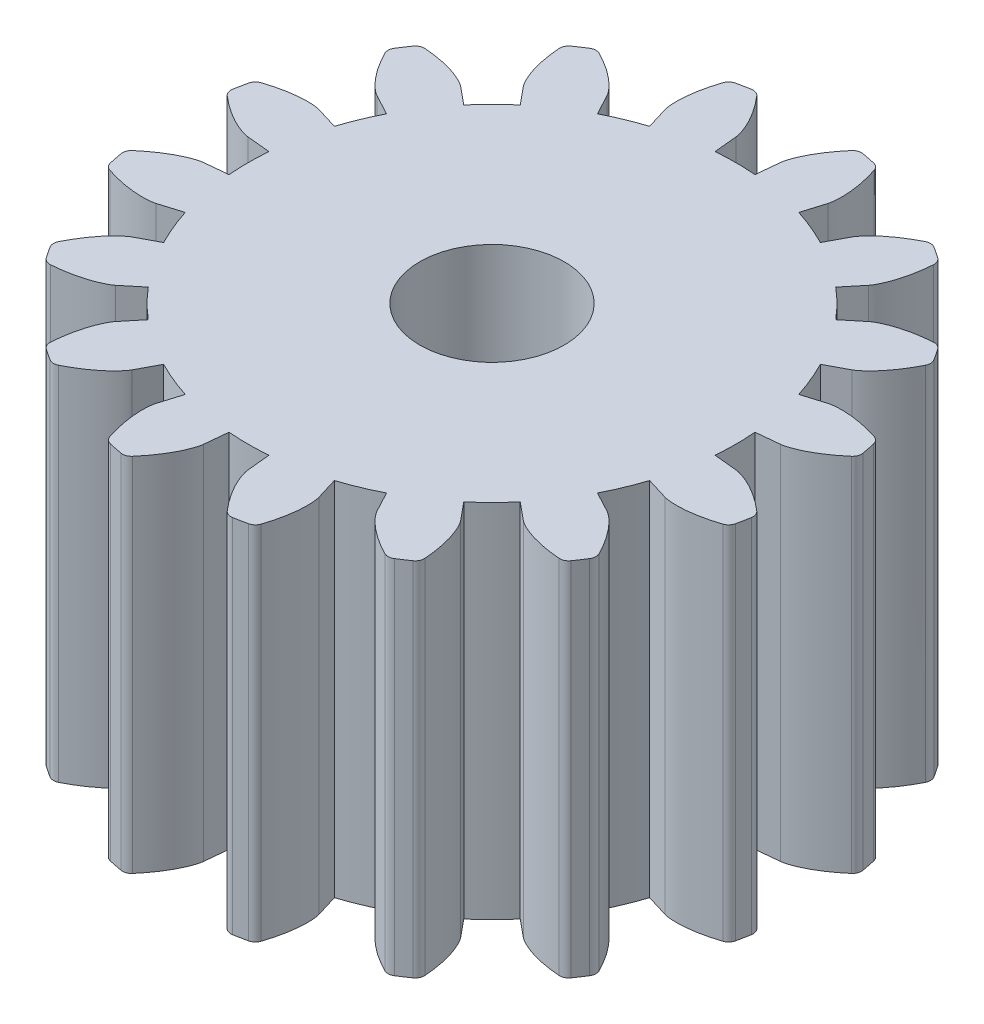
SolidWorks part; units mm, degrees
ref_plane "Front Plane" through (0, 0, 0) normal (0, 0, 1) x (1, 0, 0)
ref_plane "Top Plane" through (0, 0, 0) normal (0, 1, 0) x (1, 0, 0)
ref_plane "Right Plane" through (0, 0, 0) normal (1, 0, 0) x (0, 0, -1)
sketch "Sketch4" plane through (0, 0, 0) normal (0, 1, 0) x (1, 0, 0)
  circle A0 centre (0, 0) radius 9
  dimension "D1" = 18
extrude "Boss-Extrude2" add sketch "Sketch4" along normal blind 10.16 separate body contours A0
sketch "Sketch6" plane through (0, 10.16, 0) normal (0, 1, 0) x (1, 0, 0)
  circle A0 centre (0, 0) radius 2.032
  dimension "D1" = 4.064
extrude "Cut-Extrude1" cut sketch "Sketch6" against normal blind 10.16 contours A0
sketch "Sketch7" plane through (0, 10.16, 0) normal (0, 1, 0) x (1, 0, 0)
  line L0 (0, 0) -> (10.4884, 0) construction
  line L1 (7.4915, 0.6253) -> (6.835, 0.5613)
  line L3 (7.4915, -0.6253) -> (6.835, -0.5613)
  circle A0 centre (0, 0) radius 8 construction
  circle A1 centre (0, 0) radius 7.493 construction
  circle A2 centre (0, 0) radius 6.858 construction
  arc A3 (6.835, 0.5613) -> (6.835, -0.5613) centre (0, 0) cw
  arc A4 (8.886, 1.4282) -> (9.071, 0) centre (5.3028, 0.2379) cw
  arc A5 (8.886, -1.4282) -> (9.071, 0) centre (5.3028, -0.2379) ccw
  spline S0 degree 4 poles (7.4915, 0.6253) (7.4939, 0.6255) (7.5006, 0.6263) (7.5213, 0.6293) (7.5618, 0.6371) (7.6114, 0.6494) (7.668, 0.6661) (7.7222, 0.6842) (7.7683, 0.7009) (7.814, 0.7188) (7.8593, 0.7375) (7.9138, 0.7615) (7.9787, 0.7919) (8.0538, 0.8298) (8.1382, 0.8757) (8.2231, 0.9255) (8.3059, 0.9769) (8.3884, 1.0317) (8.4676, 1.0867) (8.5487, 1.1467) (8.6229, 1.2035) (8.7048, 1.2702) (8.7705, 1.3249) (8.8557, 1.4004) (8.9056, 1.4459) (8.9634, 1.5004) (8.9888, 1.5251) (9.0044, 1.5403) knots 0 0 0 0 0 0.005377 0.015084 0.04661 0.092111 0.119476 0.146842 0.174209 0.201575 0.228941 0.256307 0.307035 0.361767 0.4165 0.471232 0.525964 0.580697 0.635429 0.690161 0.744894 0.799626 0.854358 0.909091 0.954545 1 1 1 1 1 construction
  spline S1 degree 4 poles (7.4915, 0.6253) (7.4939, 0.6255) (7.5006, 0.6263) (7.5213, 0.6293) (7.5618, 0.6371) (7.6114, 0.6494) (7.668, 0.6661) (7.7222, 0.6842) (7.7683, 0.7009) (7.814, 0.7188) (7.8593, 0.7375) (7.9138, 0.7615) (7.9787, 0.7919) (8.0538, 0.8298) (8.1382, 0.8757) (8.2231, 0.9255) (8.3059, 0.9769) (8.3884, 1.0317) (8.4676, 1.0867) (8.5487, 1.1467) (8.6229, 1.2035) (8.7048, 1.2702) (8.7705, 1.3249) (8.8372, 1.384) (8.8695, 1.4132) (8.886, 1.4282) knots 0 0 0 0 0 0.005377 0.015084 0.04661 0.092111 0.119476 0.146842 0.174209 0.201575 0.228941 0.256307 0.307035 0.361767 0.4165 0.471232 0.525964 0.580697 0.635429 0.690161 0.744894 0.799626 0.854358 0.909091 0.909091 0.909091 0.909091 0.909091
  spline S2 degree 4 poles (7.4915, -0.6253) (7.4939, -0.6255) (7.5006, -0.6263) (7.5213, -0.6293) (7.5618, -0.6371) (7.6114, -0.6494) (7.668, -0.6661) (7.7222, -0.6842) (7.7683, -0.7009) (7.814, -0.7188) (7.8593, -0.7375) (7.9138, -0.7615) (7.9787, -0.7919) (8.0538, -0.8298) (8.1382, -0.8757) (8.2231, -0.9255) (8.3059, -0.9769) (8.3884, -1.0317) (8.4676, -1.0867) (8.5487, -1.1467) (8.6229, -1.2035) (8.7048, -1.2702) (8.7705, -1.3249) (8.8372, -1.384) (8.8695, -1.4132) (8.886, -1.4282) knots 0 0 0 0 0 0.005377 0.015084 0.04661 0.092111 0.119476 0.146842 0.174209 0.201575 0.228941 0.256307 0.307035 0.361767 0.4165 0.471232 0.525964 0.580697 0.635429 0.690161 0.744894 0.799626 0.854358 0.909091 0.909091 0.909091 0.909091 0.909091
  dimension "D1" = 16
  dimension "D2" = 14.986
  dimension "D3" = 13.716
extrude "Cut-Extrude2" cut sketch "Sketch7" against normal through all contours A4 A5 S2 L3 A3 L1 S1
fillet "Fillet1" radius 0.254 1 edges at (8.886, 5.08, -1.4282)
fillet "Fillet2" radius 0.254 1 edges at (8.886, 5.08, 1.4282)
pattern_circular "CirPattern1" count 16 over 360 about axis through (0, 10.16, 0) along (0, 1, 0) of "Cut-Extrude2", "Fillet1", "Fillet2"
equation "\"P\"= 25.4'INPUT: diameteral pitch"
equation "\"z\"= 16'INPUT: number of teeth"
equation "\"a\"= 20'INPUT: pressure angle, degrees"
equation "\"s\"= 0.4'INPUT: face width (inches)"
equation "\"D_b\"= 0.16'INPUT: gear bore diameter (inches)"
equation "\"c\"= 0.157 / \"P\"'clearance"
equation "\"D_p\"= \"z\" / \"P\"'pitch circle diameter"
equation "\"D_base\"= \"D_p\" * cos ( \"a\" )'base circle diameter"
equation "\"h_a\"= 1 / \"P\"'addendum depth"
equation "\"h_d\"= 1 / \"P\" + \"c\"'dedendum depth"
equation "\"P_c\"= pi / \"P\"'circular pitch"
equation "\"D_a\"= \"D_p\" + ( 2 * \"h_a\" )'addendum diameter"
equation "\"D_d\"= \"D_p\" - ( 2 * \"h_d\" )'dedendum diameter"
equation "\"theta\"= 360 / \"z\"'pitch angle"
equation "\"a_inv\"= ( \"D_p\" ^ 2 - \"D_base\" ^ 2 ) ^ 0.5 / \"D_base\" * 180 / pi - \"a\"'alpha angle for involute curve"
equation "\"b_inv\"= ( \"theta\" / 4 - \"a_inv\" )'beta angle (parameter for ivolute curve parameterization)"
equation "\"zeta\"= ( ( \"D_a\" / 2 ) ^ 2 - ( \"D_base\" / 2 ) ^ 2 ) ^ 0.5 / ( \"D_base\" / 2 )'zeta (domain for involute curve equation)"
equation "\"D1@Sketch4\"=\"D_a\""
equation "\"D1@Boss-Extrude2\"=\"s\""
equation "\"D1@Sketch6\"=\"D_b\""
equation "\"D1@Sketch7\"=\"D_p\""
